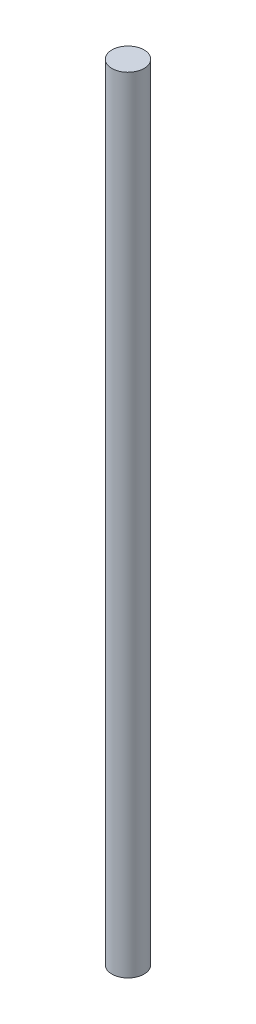
SolidWorks part; units mm, degrees
material "Plain Carbon Steel"
ref_plane "Front Plane" through (0, 0, 0) normal (0, 0, 1) x (1, 0, 0)
ref_plane "Top Plane" through (0, 0, 0) normal (0, 1, 0) x (1, 0, 0)
ref_plane "Right Plane" through (0, 0, 0) normal (1, 0, 0) x (0, 0, -1)
sketch "Sketch2" plane through (0, 0, 0) normal (0, 1, 0) x (1, 0, 0)
  circle A0 centre (0, 0) radius 4
  dimension "D1" = 8
extrude "Boss-Extrude1" add sketch "Sketch2" along normal blind 195
